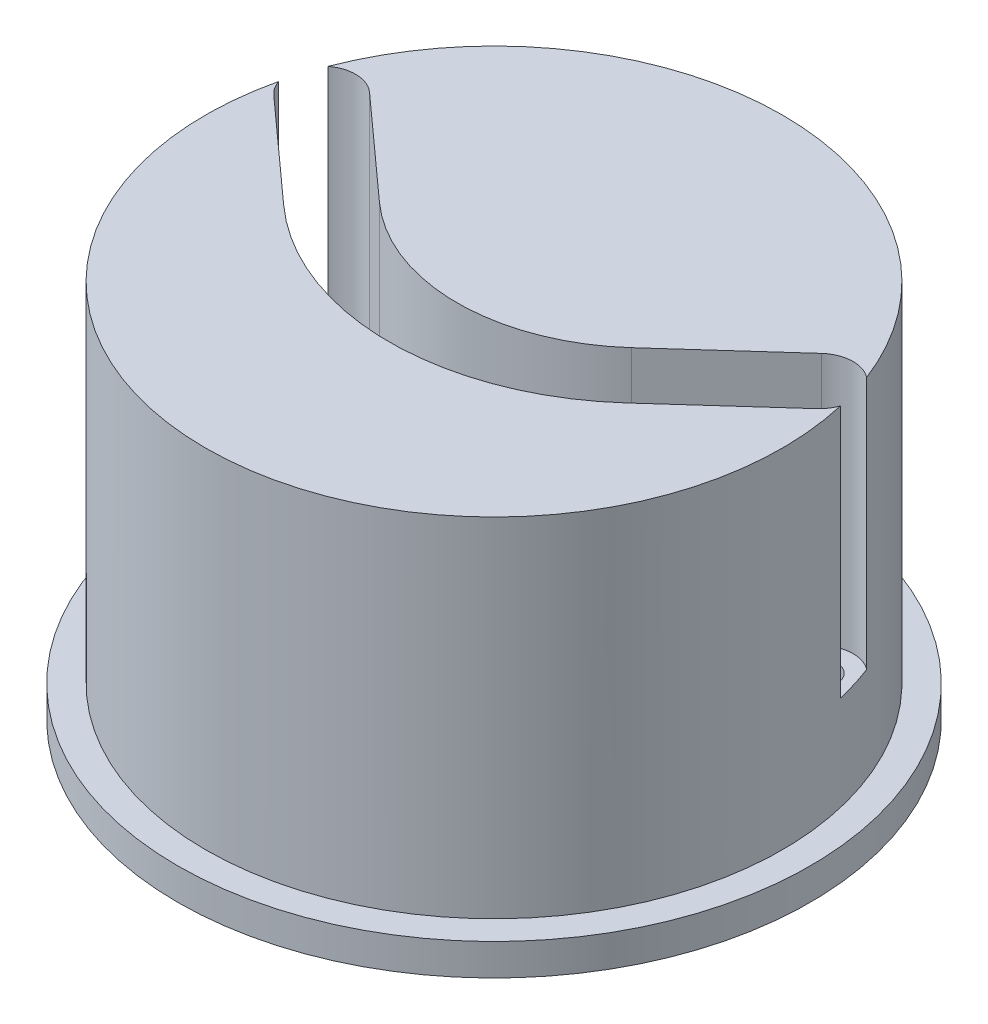
SolidWorks part; units mm, degrees
ref_plane "Front Plane" through (0, 0, 0) normal (0, 0, 1) x (1, 0, 0)
ref_plane "Top Plane" through (0, 0, 0) normal (0, 1, 0) x (1, 0, 0)
ref_plane "Right Plane" through (0, 0, 0) normal (1, 0, 0) x (0, 0, -1)
sketch "Sketch2" plane through (0, 0, 0) normal (0, 1, 0) x (1, 0, 0)
  line L0 (-6.985, 0) -> (6.985, 0) construction
  line L10 (0, 6.985) -> (0, -6.985) construction
  line L13 (0, -6.985) -> (0, 0) construction
  line L14 (-13.081, 3.175) -> (13.081, 3.175) construction
  line L15 (0, -4.445) -> (0, 3.175) construction
  line L16 (-13.081, 3.175) -> (-8.0591, -1.3498)
  line L17 (13.081, 3.175) -> (8.0591, -1.3498)
  line L18 (-11.8908, 4.4959) -> (-6.8689, -0.0289)
  line L19 (11.8908, 4.4959) -> (6.8689, -0.0289)
  line L21 (-12.4859, 3.8355) -> (12.4859, 3.8355) construction
  circle A0 centre (0, 0) radius 14.478
  arc A9 (-8.0591, -1.3498) -> (8.0591, -1.3498) centre (0, 7.5946) ccw
  arc A10 (-13.081, 3.175) -> (-11.8908, 4.4959) centre (-12.4859, 3.8355) cw
  arc A11 (-6.8689, -0.0289) -> (6.8689, -0.0289) centre (0, 7.5946) ccw
  arc A12 (11.8908, 4.4959) -> (13.081, 3.175) centre (12.4859, 3.8355) cw
  point P13 (10.1453, 10.3289)
  point P14 (7.4312, 7.4369)
  point P36 (0, 3.175)
  point P37 (-33.8663, 15.7634)
  point P42 (0, -4.445)
  point P47 (0, 3.175)
  dimension "D1" = 28.956
  dimension "D4" = 24.9718
  dimension "D9" = 12.0396
  dimension "D11" = 0.889
  dimension "D12" = 10.2616
  dimension "D3" = 3.175
  dimension "D10" = 6.7597
extrude "Boss-Extrude1" add sketch "Sketch2" along normal blind 19.05
sketch "Sketch14" plane through (0, 19.05, 0) normal (0, 1, 0) x (1, 0, 0)
  line L37 (8.6032, -1.9537) -> (13.6251, 2.5712)
  line L38 (11.3468, 5.0997) -> (6.3249, 0.5749)
  line L39 (-6.3249, 0.5749) -> (-11.3468, 5.0997)
  line L40 (-13.6251, 2.5712) -> (-8.6032, -1.9537)
  line L41 (8.6032, -1.9537) -> (13.6251, 2.5712)
  line L42 (11.3468, 5.0997) -> (6.3249, 0.5749)
  line L43 (-6.3249, 0.5749) -> (-11.3468, 5.0997)
  line L44 (-13.6251, 2.5712) -> (-8.6032, -1.9537)
  arc A43 (13.6251, 2.5712) -> (11.3468, 5.0997) centre (12.4859, 3.8355) ccw
  arc A44 (-6.3249, 0.5749) -> (6.3249, 0.5749) centre (0, 7.5946) ccw
  arc A45 (-11.3468, 5.0997) -> (-13.6251, 2.5712) centre (-12.4859, 3.8355) ccw
  arc A46 (-8.6032, -1.9537) -> (8.6032, -1.9537) centre (0, 7.5946) ccw
  arc A47 (13.6251, 2.5712) -> (11.3468, 5.0997) centre (12.4859, 3.8355) ccw
  arc A48 (-6.3249, 0.5749) -> (6.3249, 0.5749) centre (0, 7.5946) ccw
  arc A49 (-11.3468, 5.0997) -> (-13.6251, 2.5712) centre (-12.4859, 3.8355) ccw
  arc A50 (-8.6032, -1.9537) -> (8.6032, -1.9537) centre (0, 7.5946) ccw
  dimension "D1" = 0.8128
extrude "Cut-Extrude2" cut sketch "Sketch14" against normal blind 12.7
sketch "Sketch15" plane through (0, 0, 0) normal (0, -1, 0) x (1, 0, 0)
  line L0 (11.8908, -4.4959) -> (6.8689, 0.0289) construction
  line L1 (-6.8689, 0.0289) -> (-11.8908, -4.4959) construction
  line L2 (-13.081, -3.175) -> (-8.0591, 1.3498) construction
  line L3 (8.0591, 1.3498) -> (13.081, -3.175) construction
  line L4 (11.8908, -4.4959) -> (6.8689, 0.0289)
  line L5 (-6.8689, 0.0289) -> (-11.8908, -4.4959)
  line L6 (-13.081, -3.175) -> (-8.0591, 1.3498)
  line L7 (8.0591, 1.3498) -> (13.081, -3.175)
  arc A0 (8.0591, 1.3498) -> (-8.0591, 1.3498) centre (0, -7.5946) ccw construction
  arc A1 (-13.081, -3.175) -> (-11.8908, -4.4959) centre (-12.4859, -3.8355) ccw construction
  arc A2 (6.8689, 0.0289) -> (-6.8689, 0.0289) centre (0, -7.5946) ccw construction
  arc A3 (11.8908, -4.4959) -> (13.081, -3.175) centre (12.4859, -3.8355) ccw construction
  arc A4 (8.0591, 1.3498) -> (-8.0591, 1.3498) centre (0, -7.5946) ccw
  arc A5 (-13.081, -3.175) -> (-11.8908, -4.4959) centre (-12.4859, -3.8355) ccw
  arc A6 (6.8689, 0.0289) -> (-6.8689, 0.0289) centre (0, -7.5946) ccw
  arc A7 (11.8908, -4.4959) -> (13.081, -3.175) centre (12.4859, -3.8355) ccw
  circle A8 centre (0, 0) radius 15.875
  dimension "D1" = 31.75
extrude "Boss-Extrude2" add sketch "Sketch15" against normal blind 1.5875
